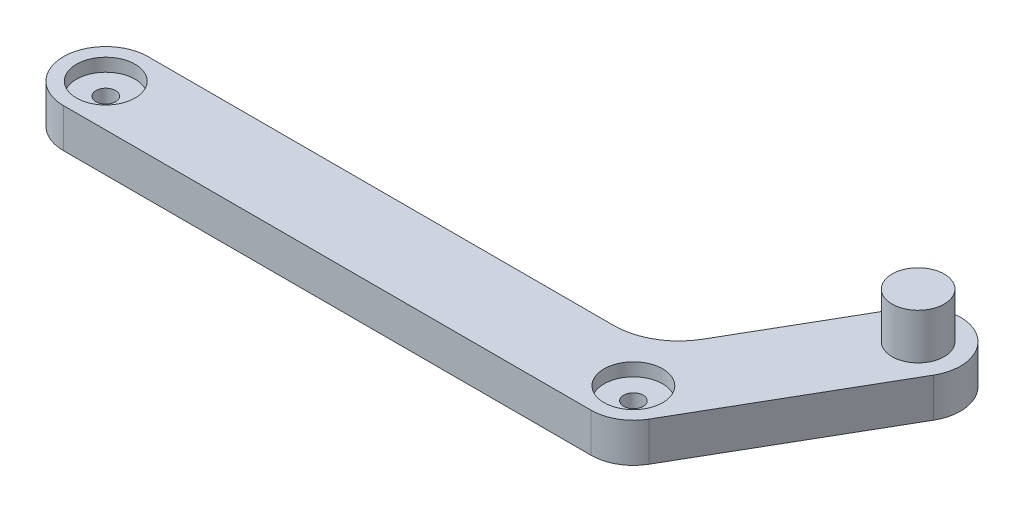
SolidWorks part; units mm, degrees
ref_plane "Front Plane" through (0, 0, 0) normal (0, 0, 1) x (1, 0, 0)
ref_plane "Top Plane" through (0, 0, 0) normal (0, 1, 0) x (1, 0, 0)
ref_plane "Right Plane" through (0, 0, 0) normal (1, 0, 0) x (0, 0, -1)
sketch "Sketch1" plane through (0, 0, 0) normal (0, 1, 0) x (1, 0, 0)
  line L0 (0, 0) -> (81, 0) construction
  line L1 (0, 6.5) -> (71.4737, 6.5)
  line L2 (0, -6.5) -> (81, -6.5)
  line L3 (81, 0) -> (97, 27.7128) construction
  line L4 (86.6292, -3.25) -> (102.6292, 24.4628)
  line L5 (80.134, 11.5) -> (91.3708, 30.9628)
  line L6 (75.3708, 3.25) -> (91.3708, 30.9628) construction
  circle A0 centre (0, 0) radius 1.5
  arc A1 (0, 6.5) -> (0, -6.5) centre (0, 0) ccw
  arc A2 (81, -6.5) -> (86.6292, -3.25) centre (81, 0) ccw
  circle A3 centre (81, 0) radius 1.5
  circle A4 centre (0, 0) radius 6.5 construction
  circle A5 centre (97, 27.7128) radius 1.5 construction
  arc A6 (102.6292, 24.4628) -> (91.3708, 30.9628) centre (97, 27.7128) ccw
  circle A7 centre (97, 27.7128) radius 6.5 construction
  arc A8 (80.134, 11.5) -> (71.4737, 6.5) centre (71.4737, 16.5) cw
  dimension "D1" = 3
  dimension "D5" = 3
  dimension "D10" = 10
  dimension "D4" = 81
  dimension "D7" = 60
  dimension "D8" = 32
  dimension "D9" = 6.5
  dimension "D2" = 5
  dimension "D6" = 5
  dimension "D3" = 2
extrude "Boss-Extrude1" add sketch "Sketch1" along normal blind 6
sketch "Sketch2" plane through (0, 6, 0) normal (0, 1, 0) x (1, 0, 0)
  circle A5 centre (0, 0) radius 4.5
  circle A6 centre (0, 0) radius 4.5
  circle A8 centre (81, 0) radius 4.5
  circle A9 centre (81, 0) radius 4.5
  dimension "D1" = 3
  dimension "D2" = 3
extrude "Cut-Extrude1" cut sketch "Sketch2" against normal blind 2
sketch "Sketch3" plane through (0, 6, 0) normal (0, 1, 0) x (1, 0, 0)
  circle A0 centre (97, 27.7128) radius 4
  arc A1 (102.6292, 24.4628) -> (91.3708, 30.9628) centre (97, 27.7128) ccw construction
  dimension "D1" = 8
extrude "Boss-Extrude2" add sketch "Sketch3" along normal blind 7
